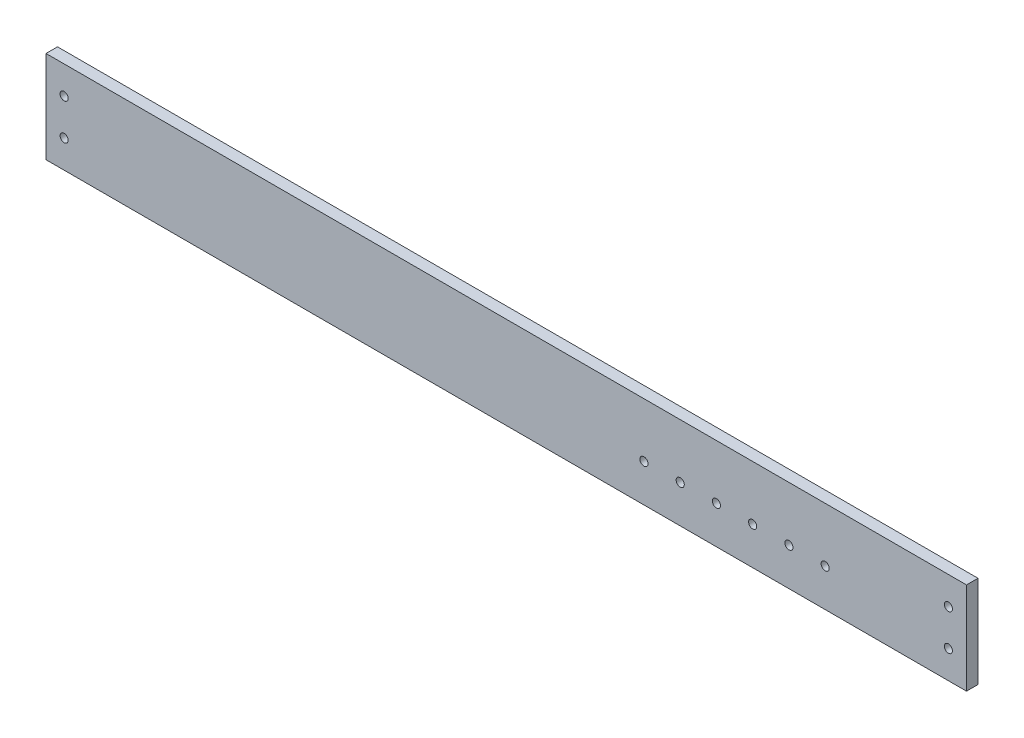
SolidWorks part; units mm, degrees
ref_plane "Front Plane" through (0, 0, 0) normal (0, 0, 1) x (1, 0, 0)
ref_plane "Top Plane" through (0, 0, 0) normal (0, 1, 0) x (1, 0, 0)
ref_plane "Right Plane" through (0, 0, 0) normal (1, 0, 0) x (0, 0, -1)
sketch "Sketch1" plane through (0, 0, 0) normal (0, 0, 1) x (1, 0, 0)
  line L0 (-144.5491, 66.7327) -> (-144.5491, 41.3327)
  line L1 (-144.5491, 66.7327) -> (109.4509, 66.7327)
  line L2 (-144.5491, 41.3327) -> (109.4509, 41.3327)
  line L3 (109.4509, 66.7327) -> (109.4509, 41.3327)
  circle A0 centre (-139.5491, 59.0327) radius 1.125
  circle A1 centre (-139.5491, 49.0327) radius 1.125
  circle A2 centre (104.4509, 59.0327) radius 1.125
  circle A3 centre (104.4509, 49.0327) radius 1.125
  circle A4 centre (20.4509, 51.7327) radius 1.125
  circle A8 centre (30.4509, 51.7327) radius 1.125
  circle A9 centre (40.4509, 51.7327) radius 1.125
  circle A10 centre (50.4509, 51.7327) radius 1.125
  circle A11 centre (60.4509, 51.7327) radius 1.125
  circle A12 centre (70.4509, 51.7327) radius 1.125
  dimension "D3" = 10
  dimension "D7" = 5
  dimension "D11" = 15
  dimension "D12" = 165
  dimension "D1" = 25.4
  dimension "D2" = 254
  dimension "D4" = 5
  dimension "D5" = 5
  dimension "D6" = 7.7
  dimension "D8" = 5
  dimension "D9" = 10
  dimension "D10" = 7.7
  dimension "D13" = 6
extrude "Boss-Extrude1" add sketch "Sketch1" along normal blind 3.175
